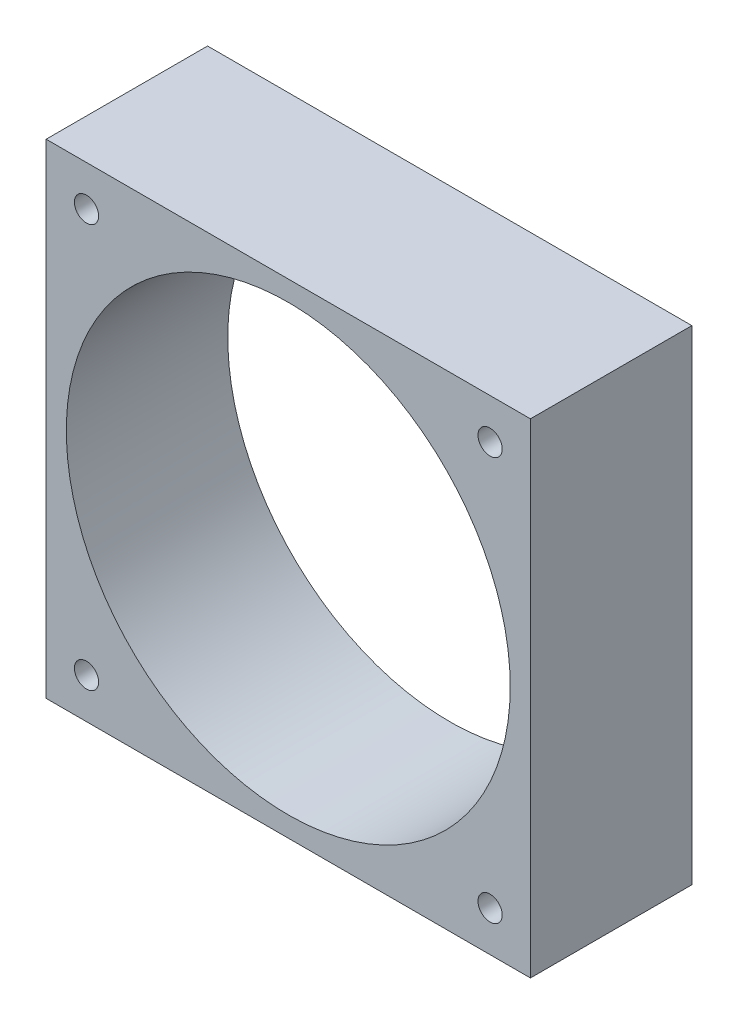
SolidWorks part; units mm, degrees
ref_plane "Plano frontal" through (0, 0, 0) normal (0, 0, 1) x (1, 0, 0)
ref_plane "Plano superior" through (0, 0, 0) normal (0, 1, 0) x (1, 0, 0)
ref_plane "Plano direito" through (0, 0, 0) normal (1, 0, 0) x (0, 0, -1)
sketch "Esboço1" plane through (0, 0, 0) normal (0, 0, 1) x (1, 0, 0)
  line L1 (-30, -30) -> (30, -30)
  line L2 (-30, -30) -> (-30, 30)
  line L3 (-30, 30) -> (30, 30)
  line L4 (30, -30) -> (30, 30)
  line L5 (-30, -30) -> (30, 30) construction
  line L6 (-30, 30) -> (30, -30) construction
  line L7 (-25, -25) -> (25, -25) construction
  line L8 (-25, -25) -> (-25, 25) construction
  line L9 (-25, 25) -> (25, 25) construction
  line L10 (25, -25) -> (25, 25) construction
  line L11 (-25, -25) -> (25, 25) construction
  line L12 (-25, 25) -> (25, -25) construction
  circle A0 centre (25, 25) radius 1.5
  circle A1 centre (-25, 25) radius 1.5
  circle A2 centre (-25, -25) radius 1.5
  circle A3 centre (25, -25) radius 1.5
  circle A4 centre (0, 0) radius 27.5
  point P0 (0, 0)
  point P6 (0, 0)
  dimension "D3" = 3
  dimension "D4" = 55
  dimension "D1" = 50
  dimension "D2" = 60
extrude "Ressalto-extrusão1" add sketch "Esboço1" along normal blind 20
